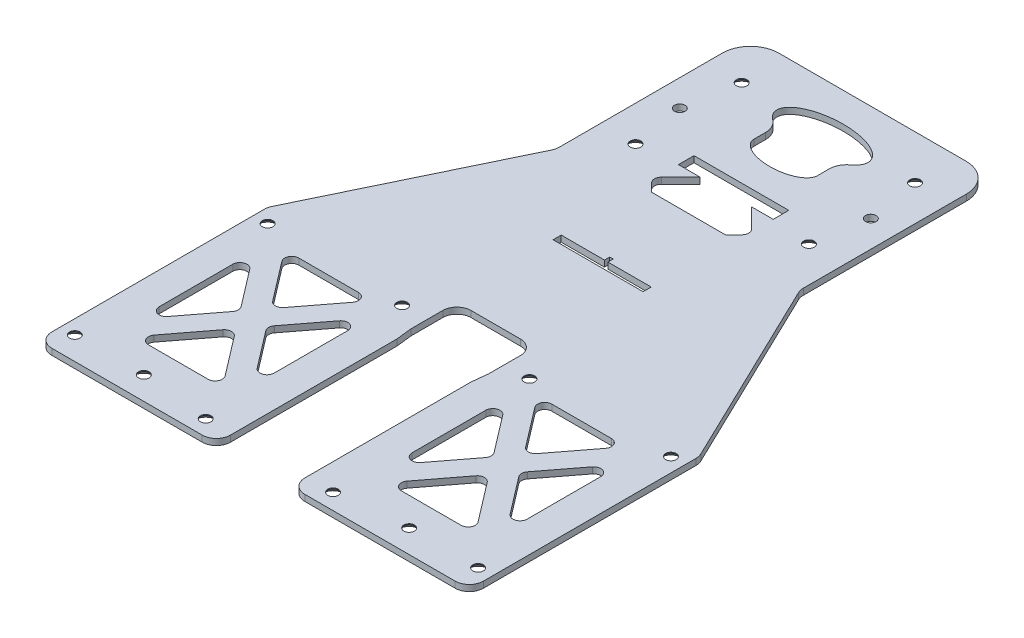
SolidWorks part; units mm, degrees
ref_plane "Front Plane" through (0, 0, 0) normal (0, 0, 1) x (1, 0, 0)
ref_plane "Top Plane" through (0, 0, 0) normal (0, 1, 0) x (1, 0, 0)
ref_plane "Right Plane" through (0, 0, 0) normal (1, 0, 0) x (0, 0, -1)
sketch "Sketch1" plane through (0, 0, 0) normal (0, 1, 0) x (1, 0, 0)
  line L0 (0, 193.2044) -> (0, -5.787) construction
  line L1 (-83.9854, 0) -> (96.1529, 0) construction
  line L2 (10.5, 0) -> (61, 0)
  line L3 (61, 0) -> (61, 65)
  line L4 (61, 65) -> (34.5, 120)
  line L5 (34.5, 120) -> (34.5, 175)
  line L6 (34.5, 175) -> (-34.5, 175)
  line L7 (10.5, 0) -> (10.5, 51)
  line L8 (10.5, 51) -> (11, 55.5)
  line L9 (11, 55.5) -> (11, 68.5)
  line L10 (11, 68.5) -> (-11, 68.5)
  line L11 (-10.5, 51) -> (-11, 55.5)
  line L12 (-11, 55.5) -> (-11, 68.5)
  line L13 (-10.5, 0) -> (-10.5, 51)
  line L14 (-10.5, 0) -> (-61, 0)
  line L15 (-61, 0) -> (-61, 65)
  line L16 (-61, 65) -> (-34.5, 120)
  line L17 (-34.5, 120) -> (-34.5, 175)
  point P18 (0, 68.5)
  point P23 (0, 175)
  dimension "D1" = 61
  dimension "D2" = 65
  dimension "D3" = 120
  dimension "D4" = 175
  dimension "D5" = 34.5
  dimension "D6" = 10.5
  dimension "D7" = 11
  dimension "D8" = 68.5
  dimension "D9" = 51
  dimension "D10" = 13
extrude "Boss-Extrude1" add sketch "Sketch1" along normal blind 1.75
sketch "Sketch2" plane through (0, 1.75, 0) normal (0, 1, 0) x (1, 0, 0)
  line L0 (0, -13.5495) -> (0, 190.4264) construction
  line L1 (10.5, 0) -> (61, 0) construction
  line L2 (61, 0) -> (61, 65) construction
  line L3 (10.5, 51) -> (10.5, 0) construction
  line L4 (23.2766, 57) -> (48.2234, 57)
  line L5 (19.5, 52.0613) -> (19.5, 19.4387)
  line L6 (23.2766, 14.5) -> (48.2234, 14.5)
  line L7 (52, 52.0613) -> (52, 19.4387)
  line L8 (19.5, 57) -> (52, 14.5) construction
  line L9 (52, 57) -> (19.5, 14.5) construction
  line L10 (19.5, 52.0613) -> (31.9734, 35.75)
  line L11 (-31.9734, 35.75) -> (-19.5, 19.4387)
  line L12 (-19.5, 52.0613) -> (-31.9734, 35.75)
  line L13 (17.1169, 55.1776) -> (49.6169, 12.6776) construction
  line L14 (-23.2766, 57) -> (-35.75, 40.6887)
  line L15 (35.75, 30.8113) -> (23.2766, 14.5)
  line L16 (-48.2234, 57) -> (-35.75, 40.6887)
  line L17 (-52, 52.0613) -> (-39.5266, 35.75)
  line L18 (23.2766, 57) -> (35.75, 40.6887)
  line L19 (-39.5266, 35.75) -> (-52, 19.4387)
  line L20 (-35.75, 30.8113) -> (-48.2234, 14.5)
  line L21 (31.9734, 35.75) -> (19.5, 19.4387)
  line L22 (-35.75, 30.8113) -> (-23.2766, 14.5)
  line L23 (35.75, 30.8113) -> (48.2234, 14.5)
  line L24 (39.5266, 35.75) -> (52, 19.4387)
  line L25 (52, 52.0613) -> (39.5266, 35.75)
  line L26 (-23.2766, 14.5) -> (-48.2234, 14.5)
  line L27 (-19.5, 52.0613) -> (-19.5, 19.4387)
  line L28 (-23.2766, 57) -> (-48.2234, 57)
  line L29 (48.2234, 57) -> (35.75, 40.6887)
  line L30 (-52, 52.0613) -> (-52, 19.4387)
  line L31 (34.5, 120) -> (34.5, 175) construction
  line L32 (24.5, 162.5) -> (24.5, 132.5) construction
  line L33 (24.5, 147.5) -> (31.9734, 147.5) construction
  line L34 (-8.9568, 150.4488) -> (-8.9568, 153.7458)
  line L35 (8.9568, 150.4488) -> (8.9568, 153.7458)
  line L36 (-10.4299, 122.9691) -> (10.4299, 122.9691)
  line L37 (10.4299, 122.9691) -> (12.7129, 125.2521)
  line L38 (12.7129, 128.0805) -> (7.2772, 133.5161)
  line L39 (7.2772, 133.5161) -> (13.3935, 133.5161)
  line L40 (13.3935, 133.5161) -> (13.3935, 137.91)
  line L41 (13.3935, 137.91) -> (-13.3935, 137.91)
  line L42 (-10.4299, 122.9691) -> (-12.7129, 125.2521)
  line L43 (-12.7129, 128.0805) -> (-7.2772, 133.5161)
  line L44 (-7.2772, 133.5161) -> (-13.3935, 133.5161)
  line L45 (-13.3935, 133.5161) -> (-13.3935, 137.91)
  line L46 (-12.7129, 97.4124) -> (12.7129, 97.4124)
  line L47 (12.7129, 97.4124) -> (12.7129, 99.6981)
  line L48 (12.7129, 99.6981) -> (0.4914, 99.6981)
  line L49 (0.4914, 99.6981) -> (0.4914, 101.1931)
  line L50 (0.4914, 101.1931) -> (-0.4914, 101.1931)
  line L51 (-12.7129, 97.4124) -> (-12.7129, 99.6981)
  line L52 (-12.7129, 99.6981) -> (-0.4914, 99.6981)
  line L53 (-0.4914, 99.6981) -> (-0.4914, 101.1931)
  circle A0 centre (18, 60) radius 1.5
  circle A1 centre (18, 4.5) radius 1.5
  circle A2 centre (37.5, 6.5) radius 1.5
  circle A3 centre (57, 6.5) radius 1.5
  circle A4 centre (57, 61) radius 1.5
  circle A5 centre (-57, 6.5) radius 1.5
  circle A6 centre (-37.5, 6.5) radius 1.5
  circle A7 centre (-18, 4.5) radius 1.5
  circle A8 centre (-57, 61) radius 1.5
  circle A9 centre (-18, 60) radius 1.5
  circle A10 centre (24.5, 162.5) radius 1.5
  circle A11 centre (24.5, 132.5) radius 1.5
  circle A12 centre (27, 147.5) radius 1.5
  circle A13 centre (-24.5, 132.5) radius 1.5
  circle A14 centre (-27, 147.5) radius 1.5
  circle A15 centre (-24.5, 162.5) radius 1.5
  arc A16 (-8.9568, 153.7458) -> (-10.973, 157.7578) centre (-13.9568, 153.7458) ccw
  arc A17 (8.9568, 153.7458) -> (10.973, 157.7578) centre (13.9568, 153.7458) cw
  arc A18 (12.7129, 125.2521) -> (12.7129, 128.0805) centre (11.2987, 126.6663) ccw
  arc A19 (-12.7129, 125.2521) -> (-12.7129, 128.0805) centre (-11.2987, 126.6663) cw
  ellipse E0 centre (0, 160.8325) end of major axis (12.8752, 160.8325) minor radius 5.8776 (10.973, 157.7578) -> (-10.973, 157.7578) ccw
  ellipse E1 centre (0, 150.4488) end of major axis (8.9568, 150.4488) minor radius 4.5061 (-8.9568, 150.4488) -> (8.9568, 150.4488) ccw
  point P101 (0, 122.9691)
  point P105 (0, 137.91)
  point P107 (14.1271, 126.6663)
  point P110 (-14.1271, 126.6663)
  point P118 (0, 97.4124)
  point P121 (0, 101.1931)
  dimension "D1" = 3
  dimension "D2" = 3
  dimension "D3" = 3
  dimension "D4" = 3
  dimension "D5" = 3
  dimension "D26" = 3
  dimension "D27" = 3
  dimension "D31" = 24.5
  dimension "D33" = 3
  dimension "D34" = 5
  dimension "D35" = 5
  dimension "D36" = 2
  dimension "D6" = 18
  dimension "D7" = 18
  dimension "D8" = 4.5
  dimension "D9" = 55.5
  dimension "D10" = 4
  dimension "D11" = 4
  dimension "D12" = 54.5
  dimension "D13" = 6.5
  dimension "D14" = 6.5
  dimension "D15" = 19.5
  dimension "D16" = 9
  dimension "D17" = 9
  dimension "D18" = 14.5
  dimension "D19" = 42.5
  dimension "D21" = 3
  dimension "D22" = 3
  dimension "D23" = 3
  dimension "D24" = 3
  dimension "D25" = 3
  dimension "D28" = 162.5
  dimension "D29" = 30
  dimension "D30" = 24.5
  dimension "D32" = 7.5
  dimension "D20" = 3
extrude "Cut-Extrude1" cut sketch "Sketch2" against normal up to next (1.75 mm away)
fillet "Fillet1" radius 4 10 edges at (34.5, 0.875, -120) (61, 0.875, -65) (11, 0.875, -68.5) (-11, 0.875, -68.5) (-34.5, 0.875, -120) (-61, 0.875, -65) (-61, 0.875, 0) (61, 0.875, 0) (-10.5, 0.875, 0) (10.5, 0.875, 0)
fillet "Fillet2" radius 2 24 edges at (31.9734, 0.875, -35.75) (39.5266, 0.875, -35.75) (48.2234, 0.875, -14.5) (23.2766, 0.875, -14.5) (52, 0.875, -52.0613) (19.5, 0.875, -52.0613) (35.75, 0.875, -30.8113) (52, 0.875, -19.4387) (19.5, 0.875, -19.4387) (35.75, 0.875, -40.6887) (48.2234, 0.875, -57) (23.2766, 0.875, -57) (-48.2234, 0.875, -14.5) (-52, 0.875, -19.4387) (-23.2766, 0.875, -14.5) (-19.5, 0.875, -19.4387) (-35.75, 0.875, -40.6887) (-39.5266, 0.875, -35.75) (-19.5, 0.875, -52.0613) (-23.2766, 0.875, -57) (-35.75, 0.875, -30.8113) (-52, 0.875, -52.0613) (-48.2234, 0.875, -57) (-31.9734, 0.875, -35.75)
chamfer "Chamfer1" distance 1.5 angle 45 14 edges at (57, 0, -59.5) (-57, 0, -59.5) (-57, 0, -5) (-37.5, 0, -5) (-18, 0, -3) (18, 0, -3) (-18, 0, -58.5) (18, 0, -58.5) (57, 0, -5) (37.5, 0, -5) (-24.5, 0, -131) (-24.5, 0, -161) (24.5, 0, -131) (24.5, 0, -161)
fillet "Fillet3" radius 8 2 edges at (34.5, 0.875, -175) (-34.5, 0.875, -175)
